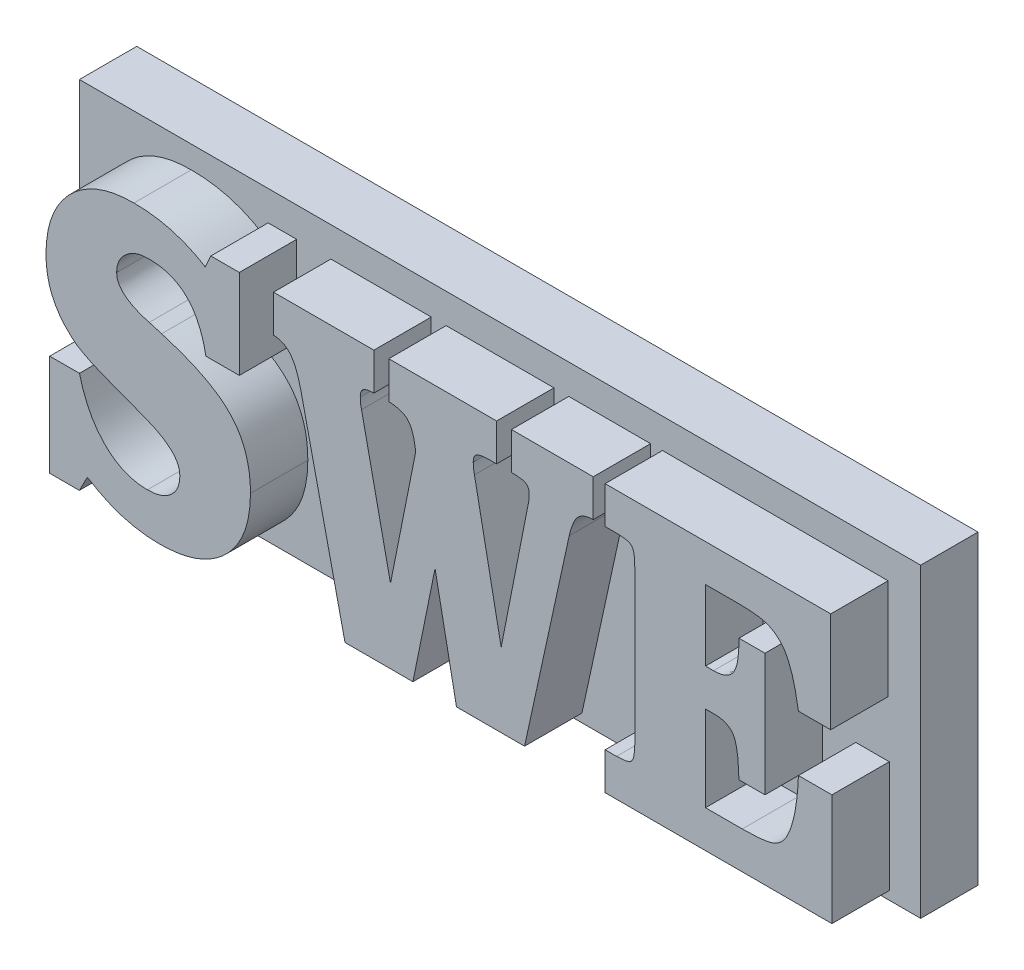
SolidWorks part; units mm, degrees
ref_plane "Front Plane" through (0, 0, 0) normal (0, 0, 1) x (1, 0, 0)
ref_plane "Top Plane" through (0, 0, 0) normal (0, 1, 0) x (1, 0, 0)
ref_plane "Right Plane" through (0, 0, 0) normal (1, 0, 0) x (0, 0, -1)
sketch "Sketch1" plane through (0, 0, 0) normal (0, 0, 1) x (1, 0, 0)
  line L1 (-69.85, -25.4) -> (69.85, -25.4)
  line L2 (-69.85, -25.4) -> (-69.85, 25.4)
  line L3 (-69.85, 25.4) -> (69.85, 25.4)
  line L4 (69.85, -25.4) -> (69.85, 25.4)
  line L5 (-69.85, -25.4) -> (69.85, 25.4) construction
  line L6 (-69.85, 25.4) -> (69.85, -25.4) construction
  point P0 (0, 0)
  dimension "D1" = 50.8
  dimension "D2" = 139.7
extrude "Boss-Extrude1" add sketch "Sketch1" along normal blind 9.525
sketch "Sketch2" plane through (0, 0, 9.525) normal (0, 0, 1) x (1, 0, 0)
  line L0 (-69.85, -23.9968) -> (69.85, -23.9968) construction
  line L1 (-69.85, 25.4) -> (-69.85, -25.4) construction
  line L2 (69.85, -25.4) -> (69.85, 25.4) construction
  text T0 "SWE" font "Clarendon Blk BT" height 44.45
extrude "Boss-Extrude2" add sketch "Sketch2" along normal blind 9.525
sketch "Sketch3" plane through (0, 0, 0) normal (0, 0, -1) x (-1, 0, 0)
  line L0 (-69.85, 25.4) -> (69.85, 25.4) construction
  line L1 (-68.326, -19.05) -> (-65.024, -19.05)
  line L2 (-68.326, -19.05) -> (-68.326, 19.05)
  line L3 (-68.326, 19.05) -> (-65.024, 19.05)
  line L4 (-65.024, -19.05) -> (-65.024, 19.05)
  line L5 (-68.326, -19.05) -> (-65.024, 19.05) construction
  line L6 (-68.326, 19.05) -> (-65.024, -19.05) construction
  line L7 (-69.85, -25.4) -> (-69.85, 25.4) construction
  line L8 (0, 25.4) -> (0, -25.4) construction
  line L9 (69.85, -25.4) -> (-69.85, -25.4) construction
  line L10 (68.326, 19.05) -> (65.024, 19.05)
  line L11 (65.024, -19.05) -> (65.024, 19.05)
  line L12 (68.326, -19.05) -> (65.024, -19.05)
  line L13 (68.326, -19.05) -> (68.326, 19.05)
  point P0 (-66.675, 0)
  dimension "D1" = 25.4
  dimension "D2" = 38.1
  dimension "D3" = 3.302
  dimension "D4" = 3.175
extrude "Cut-Extrude1" cut sketch "Sketch3" against normal blind 6.35
ref_plane "Plane1" through (0, 7.62, 0) normal (0, 1, 0) x (1, 0, 0)
sketch "Sketch6" plane through (0, 7.62, 0) normal (0, 1, 0) x (1, 0, 0)
  line L0 (49.9633, 0) -> (60.228, 0)
  line L1 (69.85, 0) -> (-69.85, 0) construction
  line L2 (69.85, -9.525) -> (69.85, 0) construction
  line L3 (53.5411, 4.7674) -> (52.7247, 5.7403)
  line L4 (56.755, 4.7674) -> (57.5713, 5.7403)
  arc A0 (53.5411, 4.7674) -> (56.755, 4.7674) centre (55.148, 2.8523) ccw
  arc A1 (58.918, 2.8523) -> (57.5713, 5.7403) centre (55.148, 2.8523) ccw
  arc A2 (50.068, 0) -> (51.378, 2.8523) centre (43.5609, 4.7156) ccw
  arc A3 (58.918, 2.8523) -> (60.228, 0) centre (66.7351, 4.7156) ccw
  circle A4 centre (55.148, 2.8523) radius 3.77 construction
  arc A5 (52.7247, 5.7403) -> (51.378, 2.8523) centre (55.148, 2.8523) ccw
  circle A6 centre (55.148, 2.8523) radius 2.5 construction
  point P9 (55.148, 0)
  point P19 (55.148, 2.8523)
  point P20 (55.098, 2.8523)
  dimension "D4" = 1.27
  dimension "D5" = 5
  dimension "D2" = 10.16
  dimension "D3" = 14.702
  dimension "D6" = 2.8523
  dimension "D1" = 1.27
extrude "Boss-Extrude4" add sketch "Sketch6" along normal blind 3.175 contours L3 A5 A2 L0 A3 A1 L4 A0
pattern_linear "LPattern1" count 3 spacing 55.372 along (-1, 0, 0) of "Boss-Extrude4"
